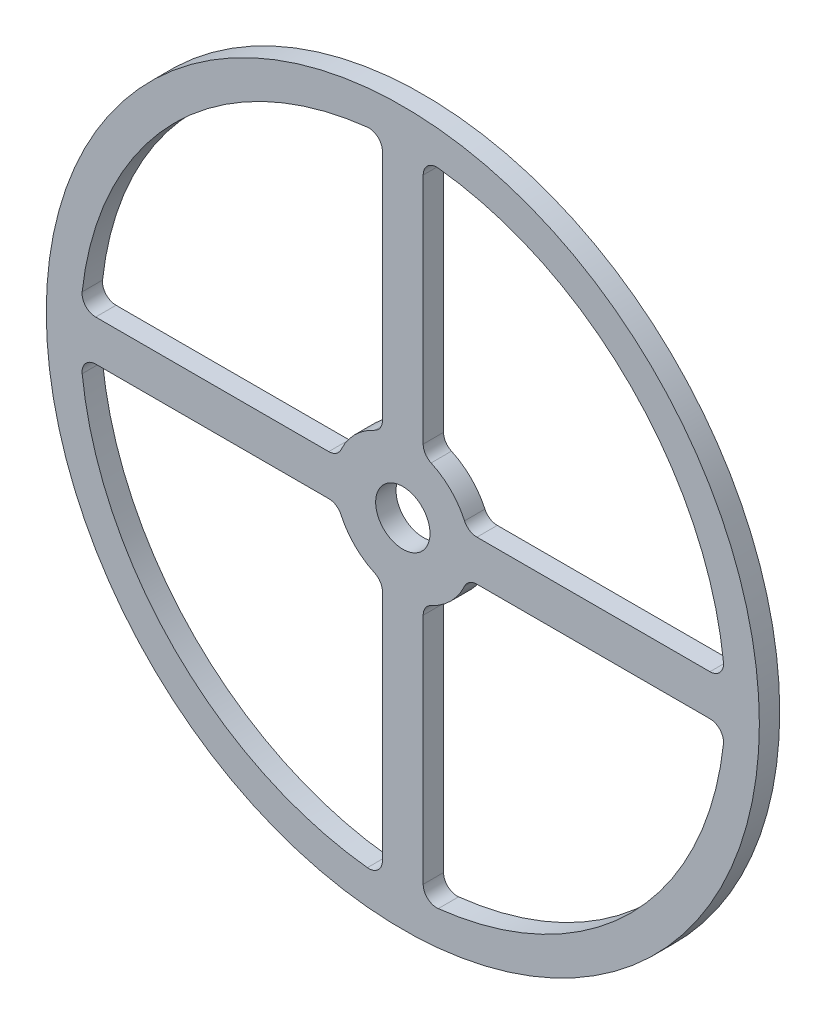
SolidWorks part; units mm, degrees
ref_plane "前视基准面" through (0, 0, 0) normal (0, 0, 1) x (1, 0, 0)
ref_plane "上视基准面" through (0, 0, 0) normal (0, 1, 0) x (1, 0, 0)
ref_plane "右视基准面" through (0, 0, 0) normal (1, 0, 0) x (0, 0, -1)
sketch "草图1" plane through (0, 0, 0) normal (0, 0, 1) x (1, 0, 0)
  line L0 (3, 47.4052) -> (3, 9.5394)
  line L1 (3, -9.5394) -> (3, -47.4052)
  line L2 (0, 61.6672) -> (0, -69.5281) construction
  line L3 (-69.9347, 0) -> (83.2168, 0) construction
  line L4 (-3, 47.4052) -> (-3, 9.5394)
  line L5 (-47.4052, -3) -> (-9.5394, -3)
  line L6 (-47.4052, 3) -> (-9.5394, 3)
  line L7 (9.5394, 3) -> (47.4052, 3)
  line L9 (-3, -9.5394) -> (-3, -47.4052)
  line L10 (9.5394, -3) -> (47.4052, -3)
  circle A0 centre (0, 0) radius 52.5
  arc A1 (-47.4052, -3) -> (-3, -47.4052) centre (0, 0) ccw
  arc A2 (-3, 9.5394) -> (-9.5394, 3) centre (0, 0) ccw
  circle A3 centre (0, 0) radius 4
  arc A4 (3, -9.5394) -> (9.5394, -3) centre (0, 0) ccw
  arc A5 (9.5394, 3) -> (3, 9.5394) centre (0, 0) ccw
  arc A6 (-9.5394, -3) -> (-3, -9.5394) centre (0, 0) ccw
  arc A7 (47.4052, 3) -> (3, 47.4052) centre (0, 0) ccw
  arc A8 (3, -47.4052) -> (47.4052, -3) centre (0, 0) ccw
  arc A9 (-3, 47.4052) -> (-47.4052, 3) centre (0, 0) ccw
  dimension "D1" = 105
  dimension "D2" = 95
  dimension "D3" = 20
  dimension "D4" = 8
  dimension "D5" = 3
  dimension "D6" = 3
extrude "凸台-拉伸1" add sketch "草图1" along normal blind 3
fillet "圆角1" radius 2 16 edges at (9.5394, -3, 1.5) (-47.4052, 3, 1.5) (-47.4052, -3, 1.5) (-9.5394, -3, 1.5) (-3, -9.5394, 1.5) (3, -9.5394, 1.5) (-3, -47.4052, 1.5) (3, -47.4052, 1.5) (-9.5394, 3, 1.5) (-3, 9.5394, 1.5) (3, 9.5394, 1.5) (9.5394, 3, 1.5) (47.4052, -3, 1.5) (47.4052, 3, 1.5) (3, 47.4052, 1.5) (-3, 47.4052, 1.5)
